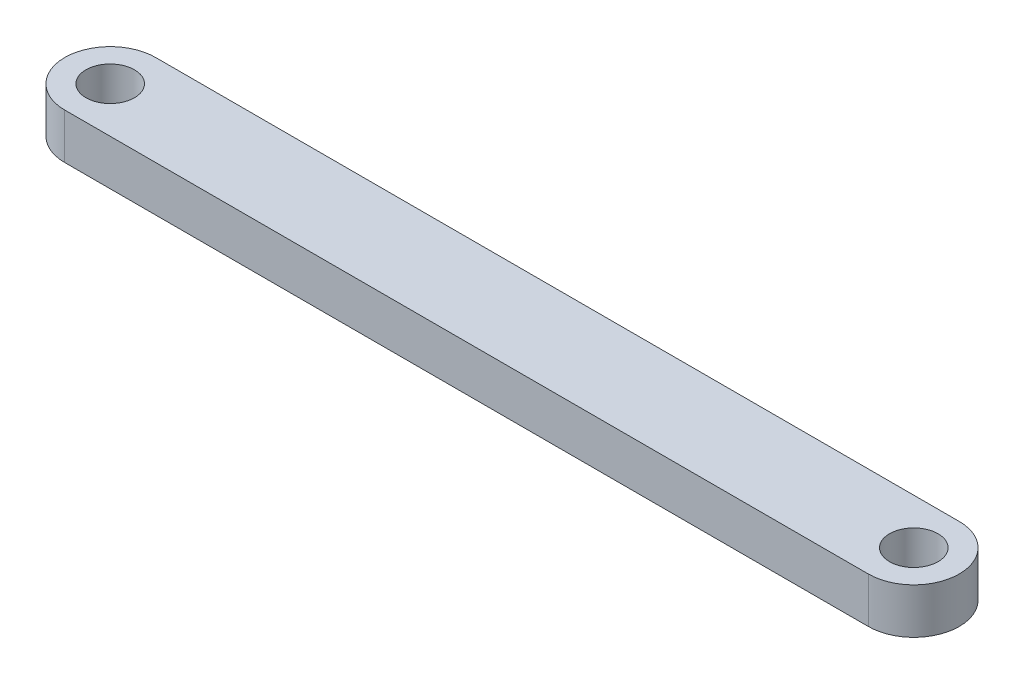
SolidWorks part; units mm, degrees
ref_plane "Front Plane" through (0, 0, 0) normal (0, 0, 1) x (1, 0, 0)
ref_plane "Top Plane" through (0, 0, 0) normal (0, 1, 0) x (1, 0, 0)
ref_plane "Right Plane" through (0, 0, 0) normal (1, 0, 0) x (0, 0, -1)
sketch "Sketch1" plane through (0, 0, 0) normal (0, 1, 0) x (1, 0, 0)
  line L0 (0, 0) -> (53, 0) construction
  line L1 (0, 3) -> (53, 3)
  line L2 (0, -3) -> (53, -3)
  arc A0 (0, 3) -> (0, -3) centre (0, 0) ccw
  arc A1 (53, -3) -> (53, 3) centre (53, 0) ccw
  circle A2 centre (0, 0) radius 1.6
  circle A3 centre (53, 0) radius 1.6
  point P3 (26.5, 0)
  dimension "D1" = 3
  dimension "D3" = 3.2
  dimension "D2" = 53
extrude "Boss-Extrude1" add sketch "Sketch1" along normal blind 3
